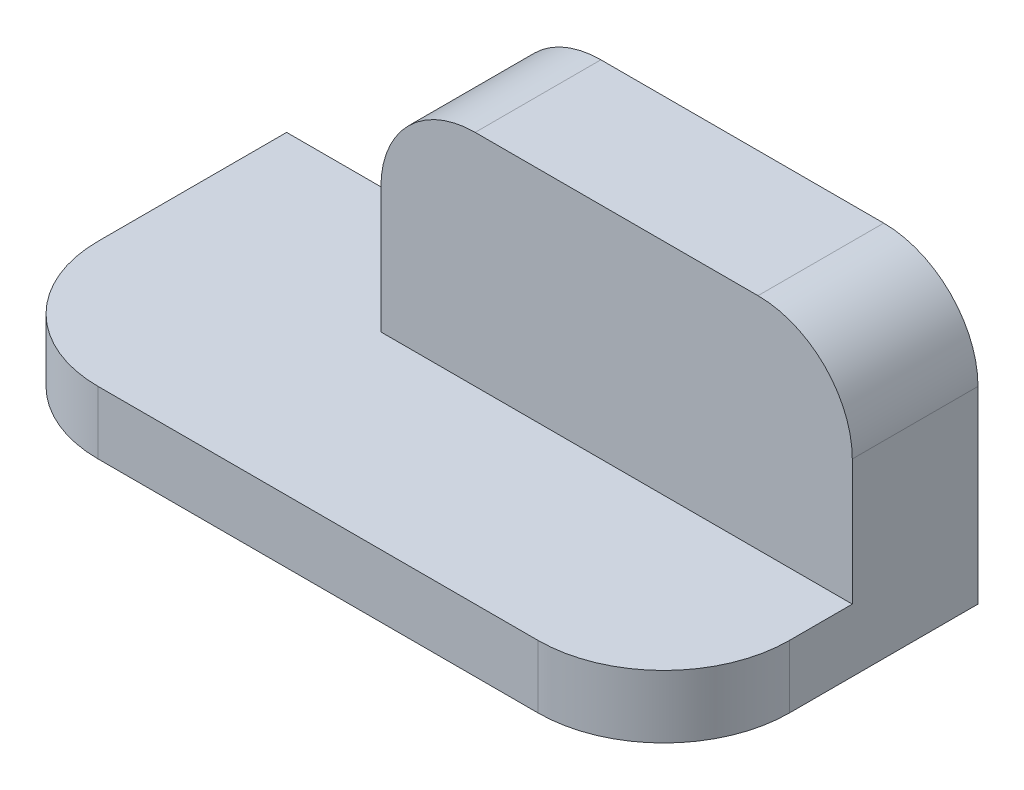
SolidWorks part; units mm, degrees
ref_plane "정면" through (0, 0, 0) normal (0, 0, 1) x (1, 0, 0)
ref_plane "윗면" through (0, 0, 0) normal (0, 1, 0) x (1, 0, 0)
ref_plane "우측면" through (0, 0, 0) normal (1, 0, 0) x (0, 0, -1)
sketch "Sketch1" plane through (0, 0, 0) normal (0, 1, 0) x (1, 0, 0)
  line L1 (0, 0) -> (110, 0)
  line L2 (0, 0) -> (0, 50)
  line L3 (0, 50) -> (110, 50)
  line L4 (110, 0) -> (110, 50)
  dimension "D1" = 50
  dimension "D2" = 110
extrude "Boss-Extrude1" add sketch "Sketch1" along normal blind 10
sketch "Sketch2" plane through (0, 10, 0) normal (0, 1, 0) x (1, 0, 0)
  line L1 (110, 50) -> (35, 50)
  line L2 (110, 50) -> (110, 30)
  line L3 (110, 30) -> (35, 30)
  line L4 (35, 50) -> (35, 30)
  dimension "D1" = 75
  dimension "D2" = 20
extrude "Boss-Extrude2" add sketch "Sketch2" along normal blind 35
fillet "Fillet2" radius 15 2 edges at (110, 45, -40) (35, 45, -40)
fillet "Fillet3" radius 20 2 edges at (110, 5, 0) (0, 5, 0)
